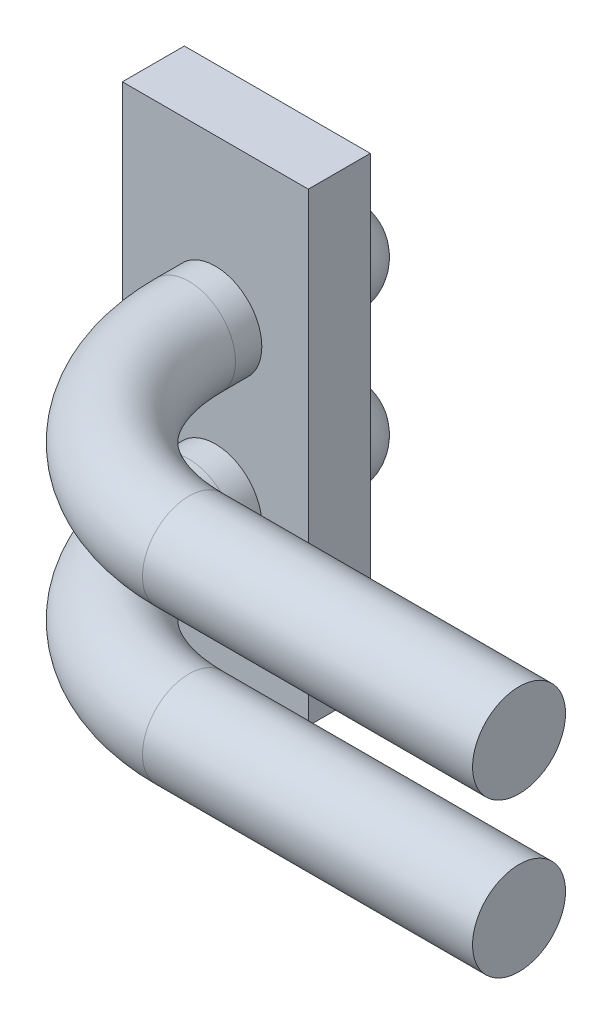
SolidWorks part; units mm, degrees
ref_plane "Front Plane" through (0, 0, 0) normal (0, 0, 1) x (1, 0, 0)
ref_plane "Top Plane" through (0, 0, 0) normal (0, 1, 0) x (1, 0, 0)
ref_plane "Right Plane" through (0, 0, 0) normal (1, 0, 0) x (0, 0, -1)
sketch "Sketch1" plane through (0, 0, 0) normal (0, 0, 1) x (1, 0, 0)
  line L1 (-3, -7.5) -> (3, -7.5)
  line L2 (-3, -7.5) -> (-3, 7.5)
  line L3 (-3, 7.5) -> (3, 7.5)
  line L4 (3, -7.5) -> (3, 7.5)
  line L5 (-3, -7.5) -> (3, 7.5) construction
  line L6 (-3, 7.5) -> (3, -7.5) construction
  point P0 (0, 0)
  dimension "D1" = 15
  dimension "D2" = 6
extrude "Boss-Extrude1" add sketch "Sketch1" along normal blind 2
sketch "Sketch2" plane through (0, 0, 0) normal (0, 0, -1) x (-1, 0, 0)
  circle A0 centre (0, 2.35) radius 1.5
  circle A1 centre (0, -2.62) radius 1.5
  dimension "D2" = 3
  dimension "D1" = 4.97
  dimension "D3" = 2.35
extrude "Boss-Extrude2" add sketch "Sketch2" along normal blind 3
fillet "Fillet1" radius 1.5 2 edges at (-1.5, -2.62, -3) (-1.5, 2.35, -3)
sketch "Sketch3" plane through (0, 0, 2) normal (0, 0, 1) x (1, 0, 0)
  circle A0 centre (0, -2.62) radius 1.5 construction
  circle A1 centre (0, 2.35) radius 1.5 construction
  circle A2 centre (0, -2.62) radius 1.5
  circle A3 centre (0, 2.35) radius 1.5
ref_plane "Plane1" through (0, 2.35, 0) normal (0, 1, 0) x (-1, 0, 0)
sketch "Sketch4" plane through (0, 2.35, 0) normal (0, 1, 0) x (-1, 0, 0)
  line L0 (0, 2) -> (0, 2.85)
  line L1 (1.5, 2) -> (-1.5, 2) construction
  line L2 (-6, 8.85) -> (-16.65, 8.85)
  arc A0 (0, 2.85) -> (-6, 8.85) centre (-6, 2.85) ccw
  point P8 (0, 8.85)
  dimension "D3" = 6
  dimension "D1" = 16.65
  dimension "D2" = 6.85
sweep "Sweep1" add profiles "Sketch3" path "Sketch4"
